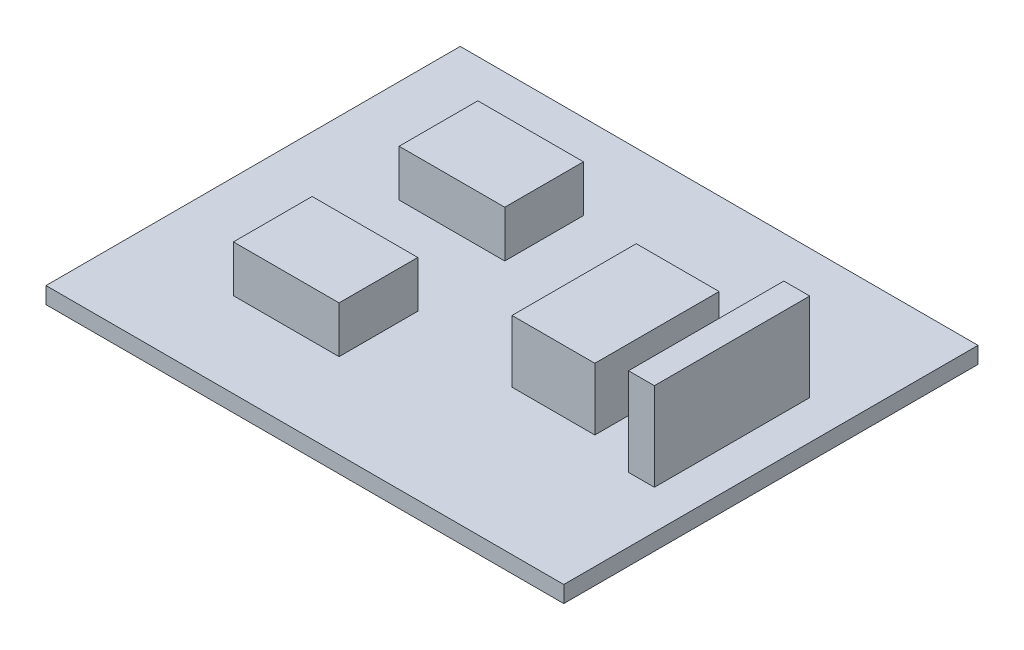
SolidWorks part; units mm, degrees
ref_plane "Front Plane" through (0, 0, 0) normal (0, 0, 1) x (1, 0, 0)
ref_plane "Top Plane" through (0, 0, 0) normal (0, 1, 0) x (1, 0, 0)
ref_plane "Right Plane" through (0, 0, 0) normal (1, 0, 0) x (0, 0, -1)
other "Configuration Table"
sketch "Sketch1" plane through (0, 0, 0) normal (0, 1, 0) x (1, 0, 0)
  line L1 (-25, -20) -> (25, -20)
  line L2 (-25, -20) -> (-25, 20)
  line L3 (-25, 20) -> (25, 20)
  line L4 (25, -20) -> (25, 20)
  line L5 (-25, -20) -> (25, 20) construction
  line L6 (-25, 20) -> (25, -20) construction
  point P6 (0, 0)
  dimension "D1" = 50
  dimension "D2" = 40
extrude "Board" add sketch "Sketch1" along normal blind 1.6
sketch "Sketch2" plane through (0, 0, 0) normal (0, 1, 0) x (1, 0, 0)
  line L0 (-15.1, 4.2) -> (-4.9, 4.2)
  line L1 (-4.9, 4.2) -> (-4.9, 11.8)
  line L2 (-4.9, 11.8) -> (-15.1, 11.8)
  line L3 (-15.1, 11.8) -> (-15.1, 4.2)
extrude "OpAmp_DIP8_1" add sketch "Sketch2" along normal blind 4.5 from offset 1.6
sketch "Sketch3" plane through (0, 0, 0) normal (0, 1, 0) x (1, 0, 0)
  line L0 (-15.1, -11.8) -> (-4.9, -11.8)
  line L1 (-4.9, -11.8) -> (-4.9, -4.2)
  line L2 (-4.9, -4.2) -> (-15.1, -4.2)
  line L3 (-15.1, -4.2) -> (-15.1, -11.8)
extrude "OpAmp_DIP8_2" add sketch "Sketch3" along normal blind 4.5 from offset 1.6
sketch "Sketch4" plane through (0, 0, 0) normal (0, 1, 0) x (1, 0, 0)
  line L0 (6, -6) -> (14, -6)
  line L1 (14, -6) -> (14, 6)
  line L2 (14, 6) -> (6, 6)
  line L3 (6, 6) -> (6, -6)
extrude "LED_Driver" add sketch "Sketch4" along normal blind 6 from offset 1.6
sketch "Sketch5" plane through (0, 0, 0) normal (0, 1, 0) x (1, 0, 0)
  line L0 (18.75, -7.5) -> (21.25, -7.5)
  line L1 (21.25, -7.5) -> (21.25, 7.5)
  line L2 (21.25, 7.5) -> (18.75, 7.5)
  line L3 (18.75, 7.5) -> (18.75, -7.5)
extrude "Header" add sketch "Sketch5" along normal blind 8.5 from offset 1.6
equation "\"Jar_OD\"= 90  'ASSUMED - Part G fallback - jar outer diameter"
equation "\"Jar_H\"= 120  'ASSUMED - Part G fallback - jar height"
equation "\"Pump_L\"= 45  'ASSUMED - Part G fallback"
equation "\"Pump_W\"= 24  'ASSUMED - Part G fallback"
equation "\"Pump_H\"= 33  'ASSUMED - Part G fallback"
equation "\"Pump_Outlet_OD\"= 7.5  'ASSUMED - Part G fallback"
equation "\"Tube_OD\"= 8  'ASSUMED - Part G fallback"
equation "\"Tube_ID\"= 6  'ASSUMED - Part G fallback"
equation "\"TDS_Body_Dia\"= 12  'ASSUMED - Part G fallback"
equation "\"TDS_Wet_Len\"= 45  'ASSUMED - Part G fallback - length in water"
equation "\"DS_Tube_Dia\"= 6  'ASSUMED - Part G fallback"
equation "\"DS_Tube_Len\"= 50  'ASSUMED - Part G fallback"
equation "\"ORP_Body_Dia\"= 12  'ASSUMED - Part G fallback"
equation "\"ORP_Body_Len\"= 150  'ASSUMED - Part G fallback"
equation "\"ORP_Cap_Dia\"= 16  'ASSUMED - Part G fallback"
equation "\"Turb_W\"= 33  'ASSUMED - Part G fallback - head width"
equation "\"Turb_D\"= 28  'ASSUMED - Part G fallback - head depth"
equation "\"Turb_H\"= 30  'ASSUMED - Part G fallback - head height"
equation "\"Turb_Slot_W\"= 10  'ASSUMED - Part G fallback - slot width"
equation "\"Flow_L\"= 62  'ASSUMED - Part G fallback YF-S201"
equation "\"Flow_W\"= 36  'ASSUMED - Part G fallback"
equation "\"Flow_H\"= 35  'ASSUMED - Part G fallback"
equation "\"Thread_G12_OD\"= 20.955  'ASSUMED - Part G fallback thread G1/2 (major diameter)"
equation "\"Valve_L\"= 75  'ASSUMED - Part G fallback"
equation "\"Valve_W\"= 45  'ASSUMED - Part G fallback"
equation "\"Valve_H\"= 60  'ASSUMED - Part G fallback"
equation "\"Tee_L\"= 40  'ASSUMED - Part G fallback - overall length"
equation "\"Tee_Branch_L\"= 25  'ASSUMED - Part G fallback"
equation "\"Tee_OD\"= 12  'ASSUMED - Part G fallback"
equation "\"LED_Board_L\"= 20  'ASSUMED - Part G fallback"
equation "\"LED_Board_W\"= 20  'ASSUMED - Part G fallback - LED at centre"
equation "\"GUVA_L\"= 20  'ASSUMED - Part G fallback"
equation "\"GUVA_W\"= 12  'ASSUMED - Part G fallback - sensor at centre"
equation "\"Reed_L\"= 27  'ASSUMED - Part G fallback MC-38 half"
equation "\"Reed_W\"= 14  'ASSUMED - Part G fallback"
equation "\"Reed_H\"= 8  'ASSUMED - Part G fallback"
equation "\"ESP_L\"= 51  'ASSUMED - Part G fallback"
equation "\"ESP_W\"= 28  'ASSUMED - Part G fallback"
equation "\"TFT_L\"= 58  'ASSUMED - Part G fallback - board"
equation "\"TFT_W\"= 35  'ASSUMED - Part G fallback - board"
equation "\"TFT_Win_L\"= 35  'ASSUMED - Part G fallback - visible window"
equation "\"TFT_Win_W\"= 28  'ASSUMED - Part G fallback - visible window"
equation "\"Relay_L\"= 50  'ASSUMED - Part G fallback"
equation "\"Relay_W\"= 26  'ASSUMED - Part G fallback"
equation "\"Relay_H\"= 19  'ASSUMED - Part G fallback"
equation "\"Mosfet_L\"= 34  'ASSUMED - Part G fallback"
equation "\"Mosfet_W\"= 17  'ASSUMED - Part G fallback"
equation "\"Mosfet_H\"= 12  'ASSUMED - Part G fallback"
equation "\"TDS_Board_L\"= 42  'ASSUMED - Part G fallback"
equation "\"TDS_Board_W\"= 32  'ASSUMED - Part G fallback"
equation "\"Turb_Board_L\"= 38  'ASSUMED - Part G fallback"
equation "\"Turb_Board_W\"= 28  'ASSUMED - Part G fallback"
equation "\"BNC_Thread_Dia\"= 9.5  'ASSUMED - Part G fallback"
equation "\"Plate_L\"= 420  'ASSUMED - Part G fallback"
equation "\"Plate_W\"= 297  'ASSUMED - Part G fallback"
equation "\"Plate_T\"= 6  'ASSUMED - Part G fallback"
equation "\"Booster_L\"= 150  'ASSUMED - Part G fallback - booster pump"
equation "\"Booster_W\"= 95  'ASSUMED - Part G fallback"
equation "\"Booster_H\"= 100  'ASSUMED - Part G fallback"
equation "\"PTube_OD\"= 6.35  'ASSUMED - Part G fallback - product tube 1/4 inch"
equation "\"Qz_Out\"= 12  'ASSUMED - Part G fallback - quartz channel outside square"
equation "\"Qz_Path\"= 10  'ASSUMED - Part G fallback - quartz channel inside light path"
equation "\"Qz_L\"= 40  'ASSUMED - Part G fallback - quartz channel length"
equation "\"LED860_Dia\"= 5  'ASSUMED - Part G fallback - 860 nm LED"
equation "\"BPW_L\"= 5.4  'ASSUMED - Part G fallback - BPW34"
equation "\"BPW_W\"= 4.3  'ASSUMED - Part G fallback - BPW34"
equation "\"Cart_Dia\"= 50  'ASSUMED - Part G fallback - sediment and pre-carbon cartridges"
equation "\"Cart_L\"= 255  'ASSUMED - Part G fallback"
equation "\"UF_Dia\"= 50  'ASSUMED - Part G fallback - UF cartridge"
equation "\"UF_L\"= 260  'ASSUMED - Part G fallback"
equation "\"RO_Dia\"= 62  'ASSUMED - Part G fallback - RO membrane housing"
equation "\"RO_L\"= 300  'ASSUMED - Part G fallback"
equation "\"UVC_Dia\"= 40  'ASSUMED - Part G fallback - UV-C chamber"
equation "\"UVC_L\"= 300  'ASSUMED - Part G fallback"
equation "\"Tank_W\"= 260  'ASSUMED - Part G fallback - storage tank"
equation "\"Tank_D\"= 160  'ASSUMED - Part G fallback"
equation "\"Tank_H\"= 300  'ASSUMED - Part G fallback"
equation "\"Cab_W\"= 400  'ASSUMED - Part G fallback - purifier cabinet"
equation "\"Cab_D\"= 270  'ASSUMED - Part G fallback"
equation "\"Cab_H\"= 560  'ASSUMED - Part G fallback"
equation "\"ORP_Board_L\"= 40  'ASSUMED - Part G fallback - ORP buffer board"
equation "\"ORP_Board_W\"= 30  'ASSUMED - Part G fallback"
equation "\"Opt_Board_L\"= 50  'ASSUMED - Part G fallback - optical front-end board"
equation "\"Opt_Board_W\"= 40  'ASSUMED - Part G fallback"
equation "\"Buck_L\"= 43  'ASSUMED - Part G fallback - 12 V to 5 V buck module"
equation "\"Buck_W\"= 21  'ASSUMED - Part G fallback"
equation "\"Buck_H\"= 14  'ASSUMED - Part G fallback"
equation "\"BB_L\"= 165  'ASSUMED - Part G fallback - breadboard (As_Built_R3 only)"
equation "\"BB_W\"= 55  'ASSUMED - Part G fallback"
equation "\"BB_H\"= 10  'ASSUMED - Part G fallback"
equation "\"Cuv_W\"= 12.5  'ASSUMED - old R3 cuvette (station suppressed in SS4)"
equation "\"Cuv_D\"= 12.5  'ASSUMED - old R3 cuvette (station suppressed in SS4)"
equation "\"Cuv_H\"= 45  'ASSUMED - old R3 cuvette (station suppressed in SS4)"
equation "\"Probe_Clr\"= 0.3  'DESIGN VALUE - Part C rule 3 - printed probe hole = diameter + 0.3"
equation "\"Label_H\"= 0.6  'DESIGN VALUE - Part D - raised label height"
equation "\"D1@Sketch1\" = \"Opt_Board_L\""
equation "\"D2@Sketch1\" = \"Opt_Board_W\""
